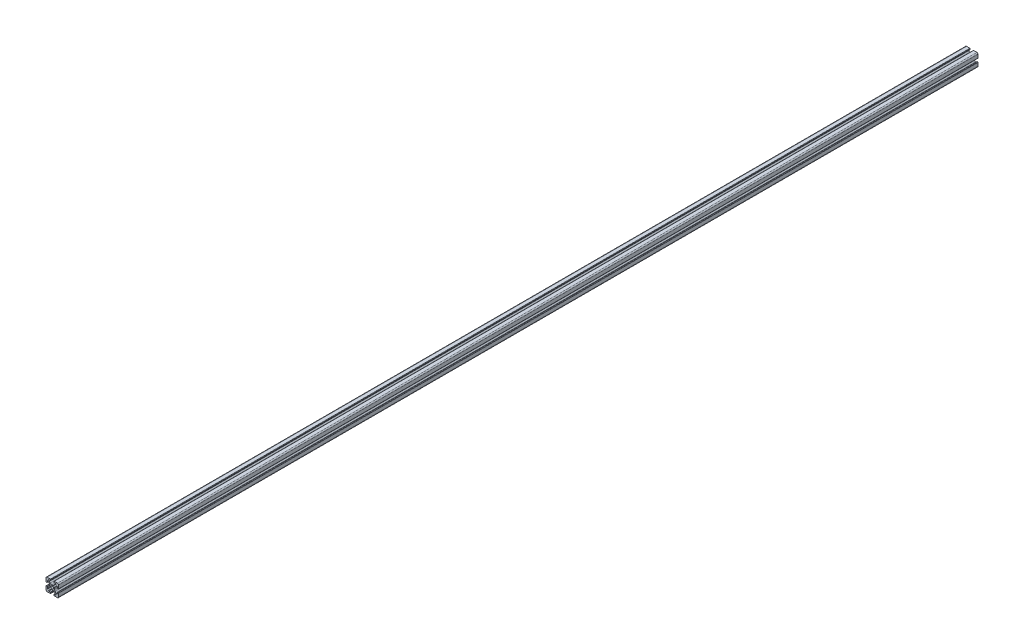
SolidWorks part; units mm, degrees
material "6061 Alloy"
ref_plane "Front Plane" through (0, 0, 0) normal (0, 0, 1) x (1, 0, 0)
ref_plane "Top Plane" through (0, 0, 0) normal (0, 1, 0) x (1, 0, 0)
ref_plane "Right Plane" through (0, 0, 0) normal (1, 0, 0) x (0, 0, -1)
sketch "Sketch2" plane through (0, 0, 0) normal (0, 0, 1) x (1, 0, 0)
  line L0 (0, 10) -> (0, -10) construction
  line L1 (-10, 0) -> (10, 0) construction
  line L2 (2.5, -10) -> (10, -10)
  line L3 (10, -10) -> (10, -2.5)
  line L4 (2.5, -10) -> (2.5, -7.9246)
  line L5 (2.5, -7.9246) -> (6.4571, -7.9246)
  line L6 (6.4571, -7.9246) -> (2.1325, -3.6)
  line L7 (0, 0) -> (10, -10) construction
  line L8 (10, -2.5) -> (7.9246, -2.5)
  line L9 (7.9246, -2.5) -> (7.9246, -6.4571)
  line L10 (7.9246, -6.4571) -> (3.6, -2.1325)
  line L11 (5.7623, -4.2948) -> (4.2948, -5.7623) construction
  circle A0 centre (0, 0) radius 2.15
  arc A1 (5.25, -7.9246) -> (5.6036, -7.0711) centre (5.25, -7.4246) ccw construction
  point P8 (0, -3.6)
  point P16 (5.0286, -5.0286)
  dimension "Center Hole Diameter" = 4.3
  dimension "D3" = 0.5
  dimension "Rail Height" = 20
  dimension "Rail Width" = 20
  dimension "T-Slot Width" = 5
  dimension "Slot Depth" = 6.4
  dimension "Slot Inner Width" = 11.5
sketch "Sketch3" plane through (0, 0, 0) normal (1, 0, 0) x (0, 0, -1)
  line L0 (-730.72, -10) -> (730.72, -10) construction
  line L1 (-705.32, 0) -> (705.32, 0) construction
  line L2 (0, 10) -> (0, -10) construction
  line L3 (0, 10) -> (0, -10) construction
  point P6 (-705.32, 0)
  point P8 (705.32, 0)
  dimension "Length" = 1461.44
  dimension "D1" = 25.4
sketch "Sketch4" plane through (0, 0, 0) normal (0, 0, 1) x (1, 0, 0)
  line L0 (3, -10) -> (8.25, -10)
  line L1 (2.5, -10) -> (10, -10) construction
  line L2 (2.5, -10) -> (2.5, -7.9246) construction
  line L3 (2.5, -7.9246) -> (6.4571, -7.9246) construction
  line L4 (2.5, -8.4246) -> (2.5, -9.5)
  line L5 (3, -7.9246) -> (5.25, -7.9246)
  line L6 (0, -3.6) -> (0.8898, -3.6)
  line L7 (6.4571, -7.9246) -> (2.1325, -3.6) construction
  line L8 (3.0112, -4.4787) -> (5.6036, -7.0711)
  line L9 (10, -10) -> (10, -2.5) construction
  line L10 (7.9246, -6.4571) -> (3.6, -2.1325) construction
  line L11 (7.9246, -2.5) -> (7.9246, -6.4571) construction
  line L12 (7.9246, -5.25) -> (7.9246, -3)
  line L13 (10, -2.5) -> (7.9246, -2.5) construction
  line L14 (8.4246, -2.5) -> (9.5, -2.5)
  line L15 (10, -3) -> (10, -8.25)
  line L16 (7.0711, -5.6036) -> (4.4787, -3.0112)
  line L17 (3.6, 0) -> (3.6, -0.8898)
  line L18 (-10, 0) -> (10, 0) construction
  line L19 (0, -3.6) -> (0, -2.15)
  line L20 (0, 10) -> (0, -10) construction
  line L21 (3.6, 0) -> (2.15, 0)
  arc A0 (2.5, -9.5) -> (3, -10) centre (3, -9.5) ccw
  arc A1 (5.25, -7.9246) -> (5.6036, -7.0711) centre (5.25, -7.4246) ccw construction
  arc A2 (2.5, -8.4246) -> (3, -7.9246) centre (3, -8.4246) cw
  arc A3 (5.25, -7.9246) -> (5.6036, -7.0711) centre (5.25, -7.4246) ccw
  arc A4 (0.8898, -3.6) -> (3.0112, -4.4787) centre (0.8898, -6.6) cw
  arc A5 (8.25, -10) -> (10, -8.25) centre (8.25, -8.25) ccw
  arc A6 (7.0711, -5.6036) -> (7.9246, -5.25) centre (7.4246, -5.25) ccw
  arc A7 (7.9246, -3) -> (8.4246, -2.5) centre (8.4246, -3) cw
  arc A8 (9.5, -2.5) -> (10, -3) centre (9.5, -3) cw
  arc A9 (4.4787, -3.0112) -> (3.6, -0.8898) centre (6.6, -0.8898) cw
  circle A10 centre (0, 0) radius 2.15 construction
  arc A11 (0, -2.15) -> (2.15, 0) centre (0, 0) ccw
  dimension "D1" = 1.75
  dimension "D2" = 3
extrude "Boss-Extrude1" add sketch "Sketch4" along normal mid plane 1461.44
mirror "Mirror1" about plane through (0, 0, 0) normal (1, 0, 0) of bodies 134
mirror "Mirror2" about plane through (0, 0, 0) normal (0, 1, 0) of bodies 135
equation "\"D3@Sketch2\"=\"T-Slot Width@Sketch2\"*0.1"
equation "\"D1@Sketch4\"=\"D3@Sketch2\"*3.5"
equation "\"D2@Sketch4\"=\"D3@Sketch2\"*6"
equation "\"D1@Boss-Extrude1\"=\"Length@Sketch3\""
